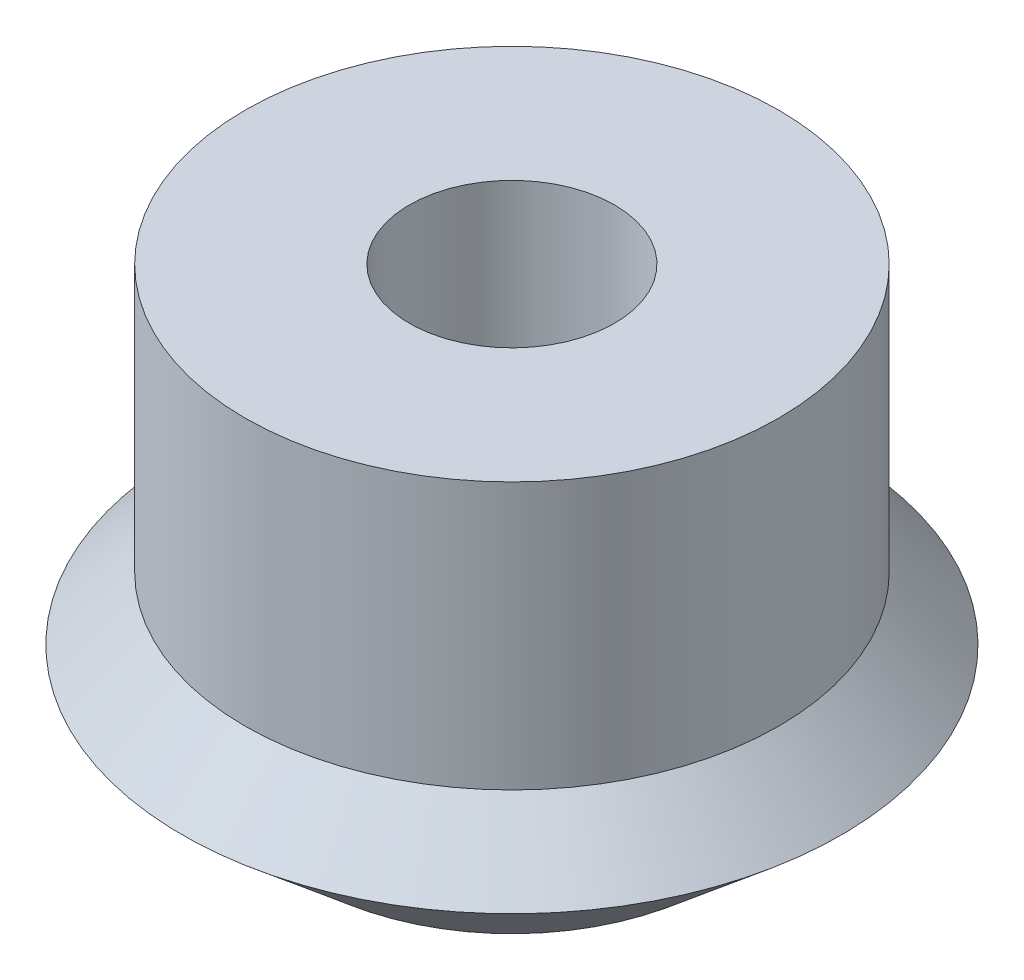
SolidWorks part; units mm, degrees
ref_plane "Front Plane" through (0, 0, 0) normal (1, 0, 0) x (0, 1, 0)
ref_plane "Top Plane" through (0, 0, 0) normal (0, 0, 1) x (0, 1, 0)
ref_plane "Right Plane" through (0, 0, 0) normal (0, 1, 0) x (-1, 0, 0)
sketch "Sketch2" plane through (0, 0, 0) normal (1, 0, 0) x (0, 1, 0)
  line L0 (-11.7435, 3.7552) -> (-14.8035, 6.8152)
  line L1 (-11.7435, 3.7552) -> (1.2565, 3.7552)
  line L4 (1.2565, 3.7552) -> (1.2565, -1.5598)
  line L5 (1.2565, -4.2448) -> (-17.7435, -4.2448)
  line L6 (1.2565, -4.2448) -> (1.2565, -1.5598)
  line L8 (-17.7435, -4.2448) -> (-17.7435, -1.5598)
  line L9 (-11.7435, 3.7552) -> (-10.6093, 2.621) construction
  line L10 (-14.8035, 6.8152) -> (-19.9672, 0.7049)
  line L11 (-14.8035, 6.8152) -> (-14.014, 6.8152) construction
  line L12 (-14.8035, 6.8152) -> (-16.5905, 6.8152) construction
  line L13 (-25.3915, -9.2448) -> (1.4719, -9.2448) construction
  line L14 (-19.9672, 0.7049) -> (-17.7435, -1.5598)
  dimension "D1" = 13
  dimension "D2" = 19
  dimension "D3" = 45
  dimension "D4" = 180
  dimension "D5" = 45
  dimension "D6" = 8
  dimension "D7" = 49.8
  dimension "D8" = 180
  dimension "D9" = 5
  dimension "D10" = 7.685
  dimension "D11" = 13
  dimension "D12" = 16.06
revolve "Revolve1" add sketch "Sketch2" angle 360 about L13
sketch "Sketch8" plane through (0, 0, 0) normal (1, 0, 0) x (0, 1, 0)
  line L0 (1.2565, -9.2448) -> (-28.7435, -9.2448) construction
  line L1 (1.2565, -22.2448) -> (1.2565, 3.7552) construction
  line L2 (1.2565, -9.2448) -> (1.2565, 3.7552) construction
  line L3 (1.2565, 3.7552) -> (-11.7435, 3.7552) construction
  line L7 (-28.7435, -9.2448) -> (-15.0534, 6.9553) construction
  line L8 (-14.8035, 6.8152) -> (-19.9672, 0.7049) construction
  dimension "D1" = 0
  dimension "D2" = 30
  dimension "D3" = 90
  dimension "D4" = 0
  dimension "D5" = 13
  dimension "D6" = 21.21
